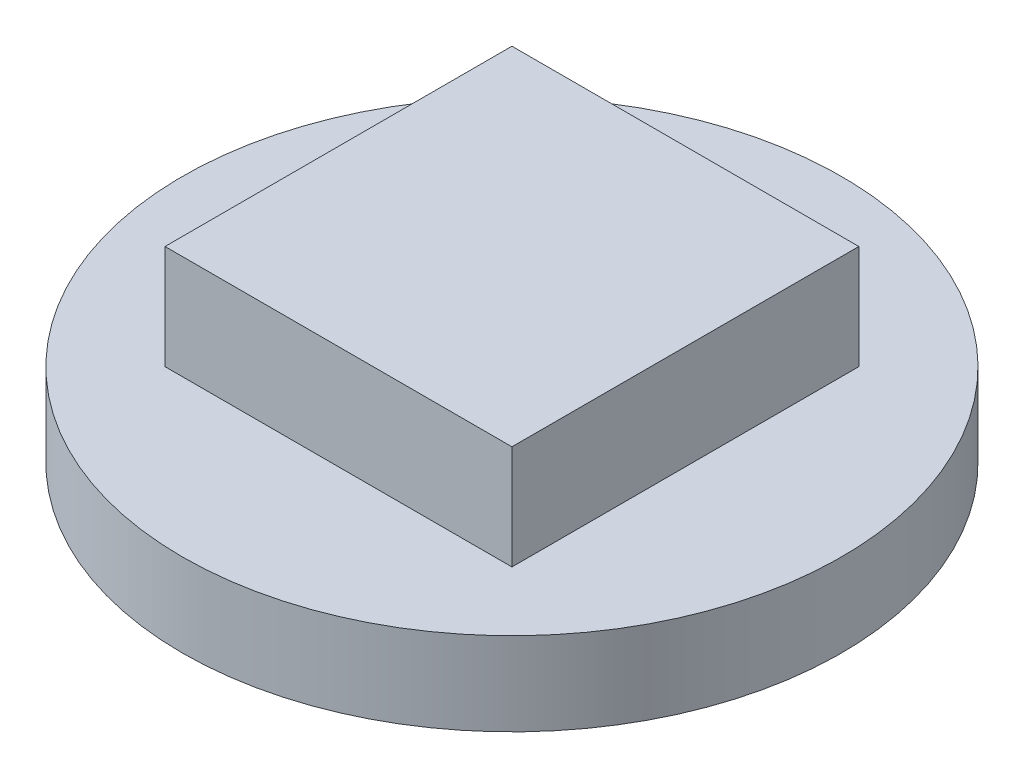
SolidWorks part; units mm, degrees
ref_plane "Front Plane" through (0, 0, 0) normal (0, 0, 1) x (1, 0, 0)
ref_plane "Top Plane" through (0, 0, 0) normal (0, 1, 0) x (1, 0, 0)
ref_plane "Right Plane" through (0, 0, 0) normal (1, 0, 0) x (0, 0, -1)
sketch "Sketch1" plane through (0, 0, 0) normal (0, 1, 0) x (1, 0, 0)
  circle A0 centre (0, 0) radius 4.75
  dimension "D1" = 9.5
extrude "Boss-Extrude1" add sketch "Sketch1" against normal blind 1.2
sketch "Sketch2" plane through (0, 0, 0) normal (0, 1, 0) x (1, 0, 0)
  line L1 (-2.5, -2.5) -> (2.5, -2.5)
  line L2 (-2.5, -2.5) -> (-2.5, 2.5)
  line L3 (-2.5, 2.5) -> (2.5, 2.5)
  line L4 (2.5, -2.5) -> (2.5, 2.5)
  line L5 (-2.5, -2.5) -> (2.5, 2.5) construction
  line L6 (-2.5, 2.5) -> (2.5, -2.5) construction
  point P0 (0, 0)
  dimension "D1" = 5
  dimension "D2" = 5
extrude "Boss-Extrude2" add sketch "Sketch2" along normal blind 1.5
